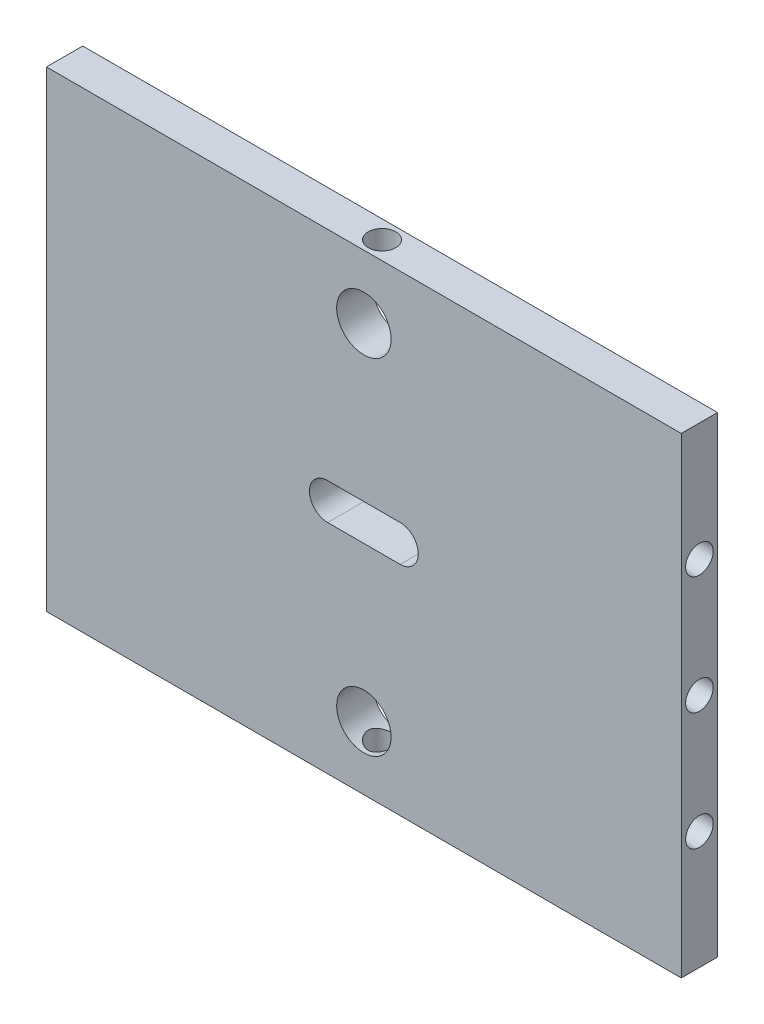
SolidWorks part; units mm, degrees
material "Plain Carbon Steel"
ref_plane "Front Plane" through (0, 0, 0) normal (0, 0, 1) x (1, 0, 0)
ref_plane "Top Plane" through (0, 0, 0) normal (0, 1, 0) x (1, 0, 0)
ref_plane "Right Plane" through (0, 0, 0) normal (1, 0, 0) x (0, 0, -1)
sketch "Sketch1" plane through (0, 0, 0) normal (0, 0, 1) x (1, 0, 0)
  line L1 (55.5625, -41.275) -> (-55.5625, -41.275)
  line L2 (55.5625, -41.275) -> (55.5625, 41.275)
  line L3 (55.5625, 41.275) -> (-55.5625, 41.275)
  line L4 (-55.5625, -41.275) -> (-55.5625, 41.275)
  line L5 (55.5625, -41.275) -> (-55.5625, 41.275) construction
  line L6 (55.5625, 41.275) -> (-55.5625, -41.275) construction
  circle A0 centre (0, 30.1625) radius 4.7625
  circle A1 centre (0, -30.1625) radius 4.7625
  point P0 (0, 0)
  dimension "D3" = 9.525
  dimension "D4" = 9.525
  dimension "D1" = 82.55
  dimension "D2" = 111.125
extrude "Boss-Extrude1" add sketch "Sketch1" along normal blind 6.35
sketch "Sketch2" plane through (55.5625, 0, 0) normal (1, 0, 0) x (0, 0, -1)
  line L0 (-3.175, 41.275) -> (-3.175, 0) construction
  line L1 (-6.35, 41.275) -> (0, 41.275) construction
  line L2 (-3.175, 0) -> (-3.175, -41.275) construction
  line L3 (-6.35, -41.275) -> (0, -41.275) construction
  circle A0 centre (-3.175, 20.6375) radius 2.413
  circle A1 centre (-3.175, 0) radius 2.413
  circle A2 centre (-3.175, -20.6375) radius 2.413
  dimension "D1" = 4.826
  dimension "D2" = 4.826
  dimension "D3" = 4.826
extrude "Cut-Extrude1" cut sketch "Sketch2" against normal blind 12.7
mirror "Mirror1" about plane through (0, 0, 0) normal (1, 0, 0) of "Cut-Extrude1"
sketch "Sketch3" plane through (0, 41.275, 0) normal (0, 1, 0) x (1, 0, 0)
  line L0 (-55.5625, -3.175) -> (55.5625, -3.175) construction
  line L1 (-55.5625, -6.35) -> (-55.5625, 0) construction
  line L2 (55.5625, -6.35) -> (55.5625, 0) construction
  circle A0 centre (0, -3.175) radius 2.413
  dimension "D1" = 4.826
extrude "Cut-Extrude2" cut sketch "Sketch3" against normal blind 12.7
mirror "Mirror2" about plane through (0, 0, 0) normal (0, 1, 0) of "Cut-Extrude2"
sketch "Sketch4" plane through (0, 0, 6.35) normal (0, 0, 1) x (1, 0, 0)
  line L0 (-6.35, 0) -> (6.35, 0) construction
  line L1 (-6.35, 3.175) -> (6.35, 3.175)
  line L2 (-6.35, -3.175) -> (6.35, -3.175)
  arc A0 (-6.35, 3.175) -> (-6.35, -3.175) centre (-6.35, 0) ccw
  arc A1 (6.35, -3.175) -> (6.35, 3.175) centre (6.35, 0) ccw
  point P3 (0, 0)
  dimension "D1" = 12.7
  dimension "D2" = 6.35
extrude "Cut-Extrude3" cut sketch "Sketch4" against normal blind 7.62
